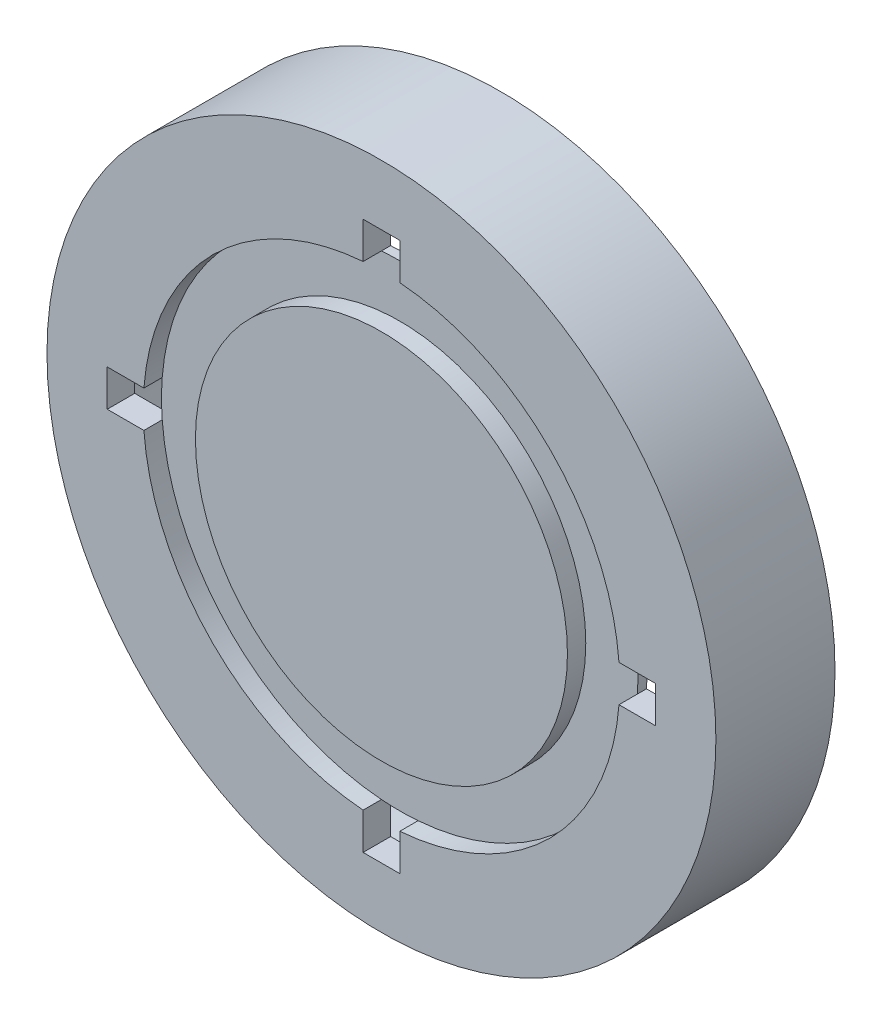
SolidWorks part; units mm, degrees
ref_plane "Front Plane" through (0, 0, 0) normal (0, 0, 1) x (1, 0, 0)
ref_plane "Top Plane" through (0, 0, 0) normal (0, 1, 0) x (1, 0, 0)
ref_plane "Right Plane" through (0, 0, 0) normal (1, 0, 0) x (0, 0, -1)
sketch "Sketch1" plane through (0, 0, 0) normal (0, 0, 1) x (1, 0, 0)
  circle A0 centre (0, 0) radius 46.355
  dimension "D1" = 92.71
extrude "Boss-Extrude1" add sketch "Sketch1" along normal blind 3.81
sketch "Sketch2" plane through (0, 0, 3.81) normal (0, 0, 1) x (1, 0, 0)
  circle A0 centre (0, 0) radius 33.02
  circle A1 centre (0, 0) radius 25.781
  dimension "D1" = 66.04
  dimension "D2" = 51.562
extrude "Cut-Extrude1" cut sketch "Sketch2" against normal blind 2.54
sketch "Sketch3" plane through (0, 0, 3.81) normal (0, 0, 1) x (1, 0, 0)
  line L0 (0, 33.02) -> (0, -33.02) construction
  line L1 (32.9222, -2.54) -> (38.0022, -2.54)
  line L2 (32.9222, -2.54) -> (32.9222, 2.54)
  line L3 (32.9222, 2.54) -> (38.0022, 2.54)
  line L4 (38.0022, -2.54) -> (38.0022, 2.54)
  line L5 (-33.02, 0) -> (32.9222, 0) construction
  line L6 (-32.9222, -2.54) -> (-32.9222, 2.54)
  line L7 (-32.9222, -2.54) -> (-38.0022, -2.54)
  line L8 (-38.0022, -2.54) -> (-38.0022, 2.54)
  line L9 (-32.9222, 2.54) -> (-38.0022, 2.54)
  line L10 (0, 38.0022) -> (0, 32.9222)
  line L11 (-2.54, 38.0022) -> (2.54, 38.0022)
  line L12 (-2.54, 38.0022) -> (-2.54, 32.9222)
  line L13 (-2.54, 32.9222) -> (2.54, 32.9222)
  line L14 (2.54, 38.0022) -> (2.54, 32.9222)
  line L15 (-2.54, -32.9222) -> (2.54, -32.9222)
  line L16 (-2.54, -38.0022) -> (-2.54, -32.9222)
  line L17 (2.54, -38.0022) -> (2.54, -32.9222)
  line L18 (-2.54, -38.0022) -> (2.54, -38.0022)
  circle A0 centre (0, 0) radius 33.02 construction
  circle A1 centre (0, 0) radius 33.02 construction
  circle M4 centre (0, 0) radius 33.02
  dimension "D1" = 5.08
  dimension "D2" = 5.08
  dimension "D3" = 5.08
  dimension "D5" = 0
extrude "Cut-Extrude2" cut sketch "Sketch3" against normal through all contours L14 L11 L10 M4 | L11 L12 L10 M4 | L9 L8 L7 M4 | L16 L18 L17 M4 | L1 L4 L3 M4
sketch "Sketch4" plane through (0, 0, 0) normal (0, 0, -1) x (-1, 0, 0)
  circle A0 centre (0, 0) radius 46.355
  circle A1 centre (0, 0) radius 44.45
  dimension "D1" = 88.9
  dimension "D2" = 92.71
extrude "Boss-Extrude2" add sketch "Sketch4" along normal blind 12.7
equation "\"D1@Boss-Extrude1\"=0.15"
